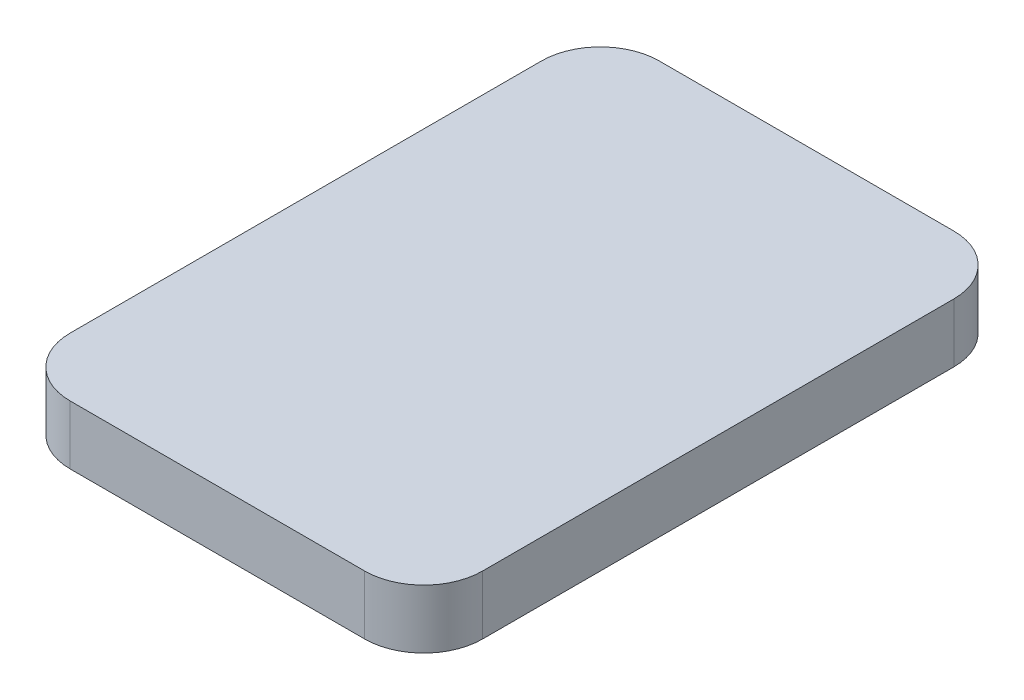
SolidWorks part; units mm, degrees
ref_plane "Plan de face" through (0, 0, 0) normal (0, 0, 1) x (1, 0, 0)
ref_plane "Plan de dessus" through (0, 0, 0) normal (0, 1, 0) x (1, 0, 0)
ref_plane "Plan de droite" through (0, 0, 0) normal (1, 0, 0) x (0, 0, -1)
sketch "Esquisse1" plane through (0, 0, 0) normal (0, 1, 0) x (1, 0, 0)
  line L0 (35, 0) -> (35, -135.9611) construction
  line L1 (0, 0) -> (70, 0)
  line L2 (30, -100) -> (40, -100)
  line L3 (70, -100) -> (70, 0)
  line L4 (40, -100) -> (70, -100)
  line L6 (30, -100) -> (0, -100)
  line L7 (0, -100) -> (0, 0)
  point P6 (35, -122.3489)
  dimension "D1" = 100
extrude "Boss.-Extru.1" add sketch "Esquisse1" along normal blind 10
fillet "Congé2" radius 10 4 edges at (0, 5, 0) (70, 5, 0) (0, 5, 100) (70, 5, 100)
